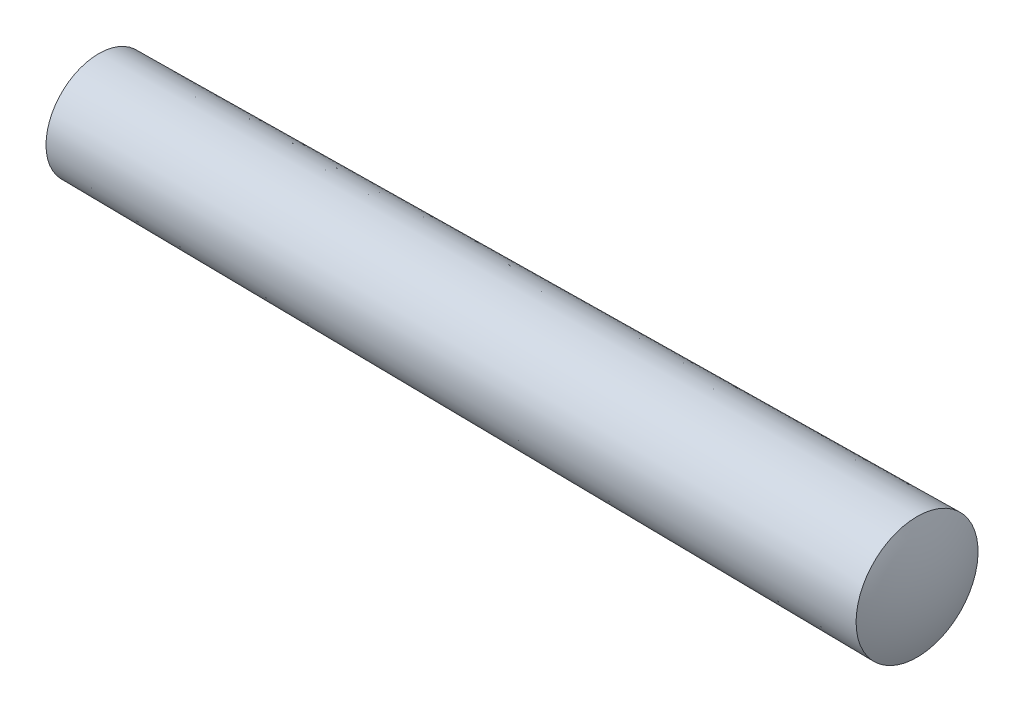
SolidWorks part; units mm, degrees
ref_plane "Plane1" through (0, 0, 0) normal (0, 0, 1) x (1, 0, 0)
ref_plane "Plane2" through (0, 0, 0) normal (0, 1, 0) x (1, 0, 0)
ref_plane "Plane3" through (0, 0, 0) normal (1, 0, 0) x (0, 0, -1)
sketch "BodySke" plane through (0, 0, 0) normal (0, 0, 1) x (1, 0, 0)
  line L0 (0, 0) -> (210, 0) construction
  line L2 (0.63, 2.5) -> (39.37, 2.8874)
  line L4 (0, 0) -> (40, 0)
  line L5 (0.63, -2.5) -> (39.37, -2.8874) construction
  arc A0 (0.63, 2.5) -> (0, 0) centre (5.2753, 0) ccw
  arc A1 (39.37, 2.8874) -> (40, 0) centre (33.0683, 0) cw
  dimension "Diameter" = 5
  dimension "Length" = 40
  dimension "Crown_ht" = 0.63
  dimension "D1" = 0.63
  dimension "D2" = 0.573
revolve "Body" add sketch "BodySke" angle 360 about L0
equation "\"D1@BodySke\" = \"Crown_ht@BodySke\""
